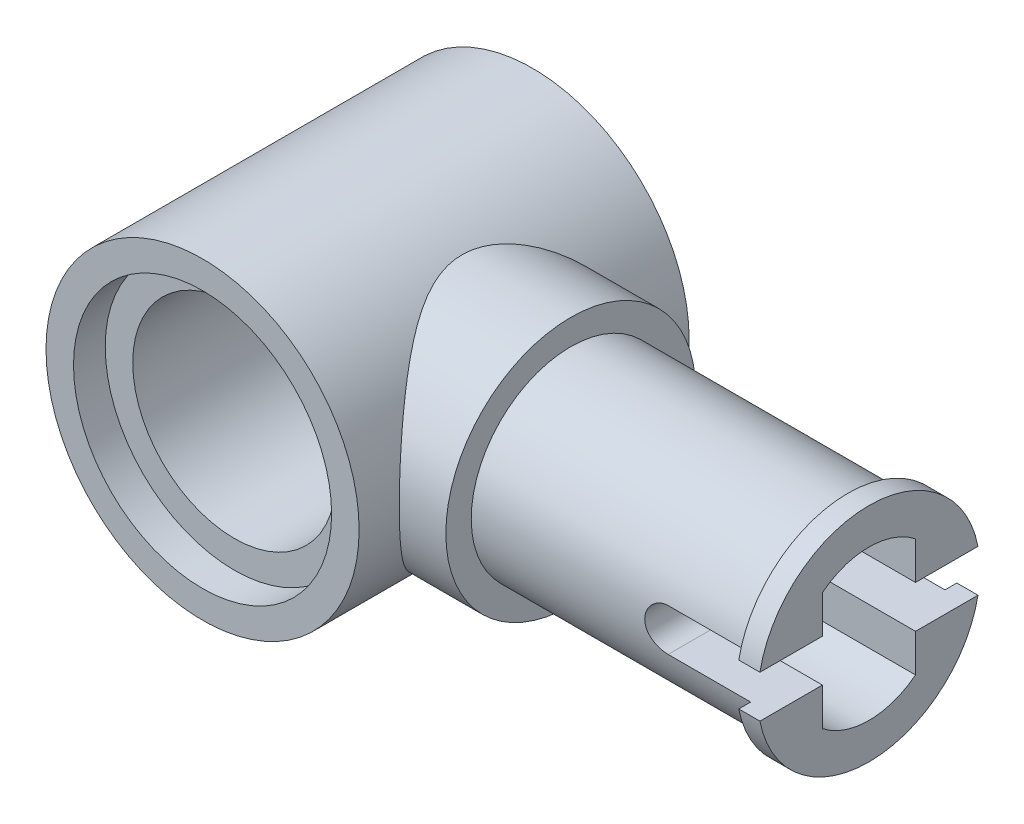
SolidWorks part; units mm, degrees
ref_plane "Front Plane" through (0, 0, 0) normal (0, 0, 1) x (1, 0, 0)
ref_plane "Top Plane" through (0, 0, 0) normal (0, 1, 0) x (1, 0, 0)
ref_plane "Right Plane" through (0, 0, 0) normal (1, 0, 0) x (0, 0, -1)
sketch "Sketch1" plane through (0, 0, 0) normal (1, 0, 0) x (0, 0, -1)
  circle A0 centre (0, 0) radius 2.35
  dimension "D1" = 4.7
extrude "Pin" add sketch "Sketch1" along normal blind 11.35
sketch "Sketch2" plane through (0, 0, 0) normal (1, 0, 0) x (0, 0, -1)
  circle A0 centre (0, 0) radius 2.95
  dimension "D1" = 5.9
extrude "Middle " add sketch "Sketch2" along normal blind 4.8
sketch "Sketch3" plane through (11.35, 0, 0) normal (1, 0, 0) x (0, 0, -1)
  circle A0 centre (0, 0) radius 2.625
  dimension "D1" = 5.25
extrude "Outer Rim" add sketch "Sketch3" along normal blind 0.5
sketch "Sketch4" plane through (0, 0, 0) normal (1, 0, 0) x (0, 0, -1)
  line L1 (1.1, -2.3834) -> (-1.1, -2.3834)
  line L2 (1.1, -2.3834) -> (1.1, 2.3834)
  line L3 (1.1, 2.3834) -> (-1.1, 2.3834)
  line L4 (-1.1, -2.3834) -> (-1.1, 2.3834)
  line L5 (1.1, -2.3834) -> (-1.1, 2.3834) construction
  line L6 (1.1, 2.3834) -> (-1.1, -2.3834) construction
  circle A1 centre (0, 0) radius 2.625 construction
  circle A2 centre (0, 0) radius 1.775
  circle A3 centre (0, 0) radius 1.775
  dimension "D2" = 2.2
  dimension "D1" = 0.85
extrude "Bore Cut " cut sketch "Sketch4" along normal through all contours L2 A3 L4
sketch "Sketch5" plane through (0, 0, 0) normal (0, 0, 1) x (1, 0, 0)
  line L0 (14.3, 0) -> (9.4, 0) construction
  line L1 (11.85, -2.625) -> (11.85, 2.625) construction
  line L2 (14.3, -0.5) -> (9.4, -0.5)
  line L3 (14.3, 0.5) -> (9.4, 0.5)
  line L4 (0, 0) -> (0, 5.0044) construction
  line L5 (-14.3, 0) -> (-9.4, 0) construction
  line L6 (-14.3, -0.5) -> (-9.4, -0.5)
  line L7 (-14.3, 0.5) -> (-9.4, 0.5)
  arc A0 (14.3, -0.5) -> (14.3, 0.5) centre (14.3, 0) ccw
  arc A1 (9.4, 0.5) -> (9.4, -0.5) centre (9.4, 0) ccw
  arc A2 (-14.3, -0.5) -> (-14.3, 0.5) centre (-14.3, 0) cw
  arc A3 (-9.4, 0.5) -> (-9.4, -0.5) centre (-9.4, 0) cw
  point P5 (11.85, 0)
  point P14 (-11.85, 0)
  dimension "D2" = 17.8
  dimension "D1" = 1
extrude "Slot Cut " cut sketch "Sketch5" against normal through all both and the other way through all
sketch "Sketch6" plane through (0, 0, 0) normal (0, 0, 1) x (1, 0, 0)
  circle A0 centre (0, 0) radius 3.7
  dimension "D1" = 7.4
extrude "Middle Body" add sketch "Sketch6" along normal mid plane 7.8
sketch "Sketch7" plane through (0, 0, 0) normal (0, 0, 1) x (1, 0, 0)
  circle A0 centre (0, 0) radius 2.4
  dimension "D1" = 4.8
extrude "Middle Bore " cut sketch "Sketch7" against normal through all both and the other way through all
sketch "Sketch8" plane through (0, 0, 3.9) normal (0, 0, 1) x (1, 0, 0)
  circle A0 centre (0, 0) radius 3.05
  dimension "D1" = 6.1
extrude "Middle Rim Cut " cut sketch "Sketch8" against normal blind 0.75
mirror "Mirror2" about plane through (0, 0, 0) normal (0, 0, 1) of "Middle Rim Cut "
